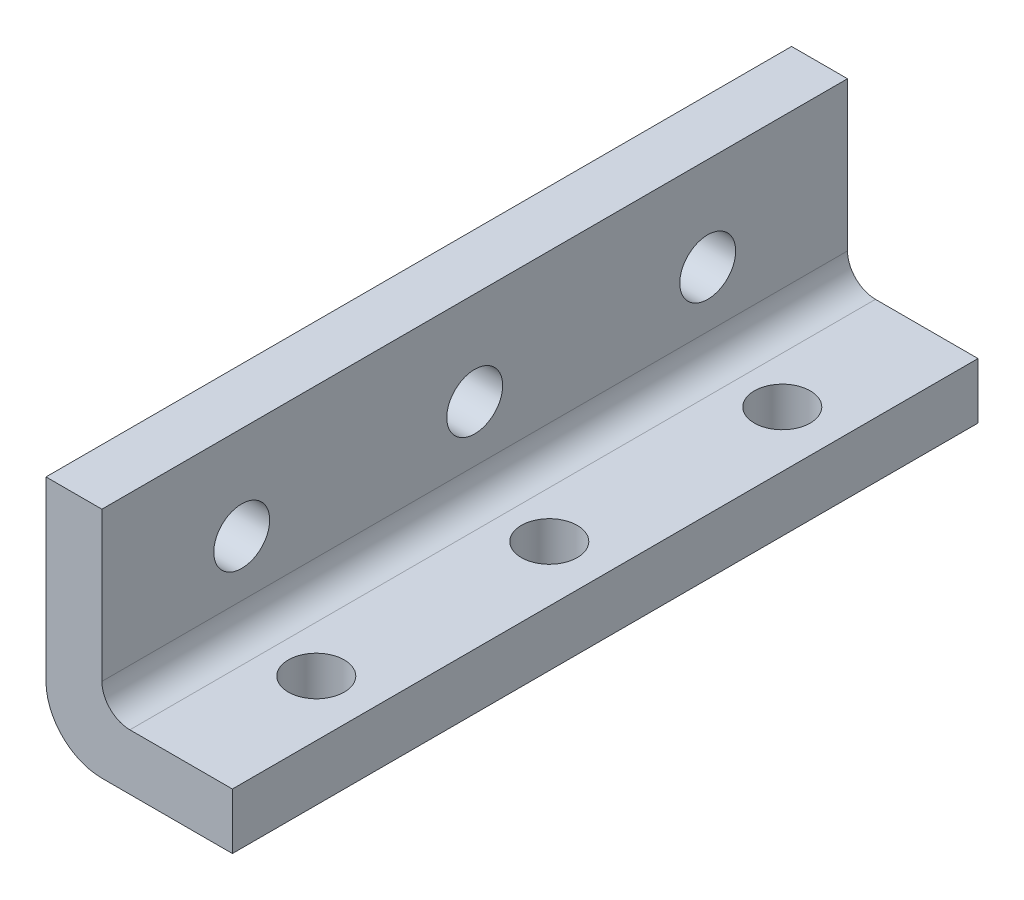
SolidWorks part; units mm, degrees
ref_plane "前视基准面" through (0, 0, 0) normal (0, 0, 1) x (1, 0, 0)
ref_plane "上视基准面" through (0, 0, 0) normal (0, 1, 0) x (1, 0, 0)
ref_plane "右视基准面" through (0, 0, 0) normal (1, 0, 0) x (0, 0, -1)
other "Configuration Table"
sketch "草图1" plane through (0, 0, 0) normal (0, 0, 1) x (1, 0, 0)
  line L0 (0, 0) -> (6, 0)
  line L1 (6, 0) -> (6, -19)
  line L2 (6, -19) -> (20, -19)
  line L3 (20, -19) -> (20, -25)
  line L4 (20, -25) -> (0, -25)
  line L5 (0, -25) -> (0, 0)
  dimension "D1" = 20
  dimension "D2" = 25
  dimension "D3" = 6
  dimension "D4" = 6
extrude "凸台-拉伸1" add sketch "草图1" along normal blind 80
sketch "草图2" plane through (6, 0, 0) normal (1, 0, 0) x (0, 0, -1)
  line L0 (-80, -19) -> (-80, 0) construction
  line L1 (-80, 0) -> (0, 0) construction
  line L2 (-40, 0) -> (-40, -17.036) construction
  circle A0 centre (-65, -10) radius 3
  circle A1 centre (-15, -10) radius 3
  circle A2 centre (-40, -10) radius 3
  dimension "D1" = 6
  dimension "D2" = 6
  dimension "D4" = 15
  dimension "D5" = 10
  dimension "D7" = 6
  dimension "D3" = 50
  dimension "D6" = 10
  dimension "D8" = 10
extrude "切除-拉伸1" cut sketch "草图2" against normal through all
sketch "草图3" plane through (0, -19, 0) normal (0, 1, 0) x (1, 0, 0)
  line L0 (20, -40) -> (9.1106, -40) construction
  line L1 (20, -80) -> (20, 0) construction
  line L2 (20, -80) -> (6, -80) construction
  circle A0 centre (14, -15) radius 3
  circle A1 centre (14, -65) radius 3
  circle A2 centre (14, -40) radius 3
  dimension "D1" = 6
  dimension "D2" = 6
  dimension "D6" = 6
  dimension "D3" = 50
  dimension "D4" = 6
  dimension "D5" = 15
  dimension "D7" = 6
extrude "切除-拉伸2" cut sketch "草图3" against normal through all
fillet "圆角1" radius 6 1 edges at (0, -25, 40)
fillet "圆角3" radius 3 1 edges at (6, -19, 40)
